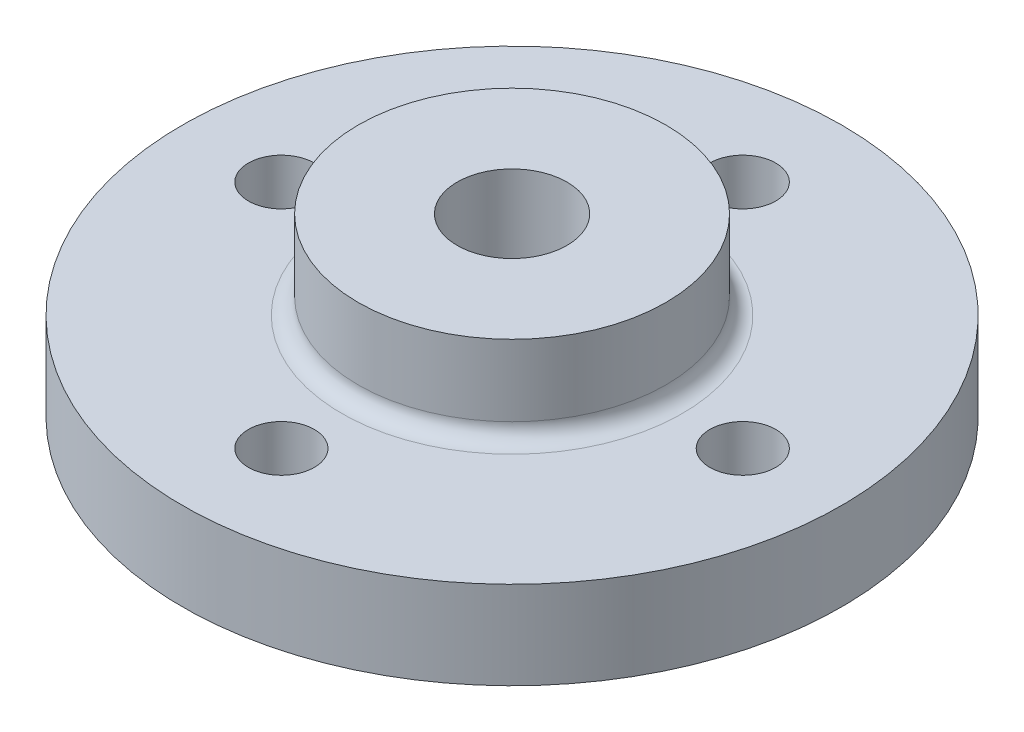
SolidWorks part; units mm, degrees
ref_plane "Front Plane" through (0, 0, 0) normal (0, 0, 1) x (1, 0, 0)
ref_plane "Top Plane" through (0, 0, 0) normal (0, 1, 0) x (1, 0, 0)
ref_plane "Right Plane" through (0, 0, 0) normal (1, 0, 0) x (0, 0, -1)
sketch "Sketch1" plane through (0, 0, 0) normal (0, 0, 1) x (1, 0, 0)
  line L0 (0, 0) -> (0, 22189.3576) construction
  line L1 (-1046, 0) -> (-23, 0) construction
  line L2 (-60, 0) -> (-60, 16)
  line L3 (-60, 16) -> (-31, 16)
  line L4 (-28, 19) -> (-28, 32)
  line L5 (-28, 32) -> (-10, 32)
  line L6 (-10, 32) -> (-10, 12)
  line L7 (-23, 0) -> (-60, 0)
  line L8 (-23, 0) -> (-23, 12)
  line L9 (-23, 12) -> (-10, 12)
  line L10 (-10, 0) -> (22189.3576, 0) construction
  arc A0 (-31, 16) -> (-28, 19) centre (-31, 19) ccw
  point P13 (0, 0)
  dimension "D8" = 3
  dimension "D1" = 20
  dimension "D2" = 56
  dimension "D3" = 120
  dimension "D4" = 16
  dimension "D5" = 32
  dimension "D6" = 12
  dimension "D7" = 46
revolve "Revolve1" add sketch "Sketch1" angle 360 about L0
sketch "Sketch2" plane through (0, 0, 0) normal (0, -1, 0) x (1, 0, 0)
  circle A0 centre (0, 0) radius 42 construction
  point P3 (0, 42)
  dimension "D1" = 84
hole_wizard "Ø12.0mm Dowel Hole1" positions "Sketch2" profile "Sketch3" hole size "Ø12.0" standard "ISO" end condition through all
sketch "Sketch3" plane through (0, 0, 42) normal (1, 0, 0) x (0, 0, -1)
  line L0 (0, 0) -> (0, 32)
  line L1 (0, 32) -> (6, 32)
  line L2 (6, 32) -> (6, 0)
  line L5 (6, 0) -> (0, 0)
  line L11 (0, -6.35) -> (0, 107.95) construction
  dimension "Thru Hole Dia." = 12
  dimension "Thru Hole Depth" = 32
pattern_circular "CirPattern1" count 4 over 360 about axis through (0, 0, 0) along (0, 1, 0) of "Ø12.0mm Dowel Hole1"
